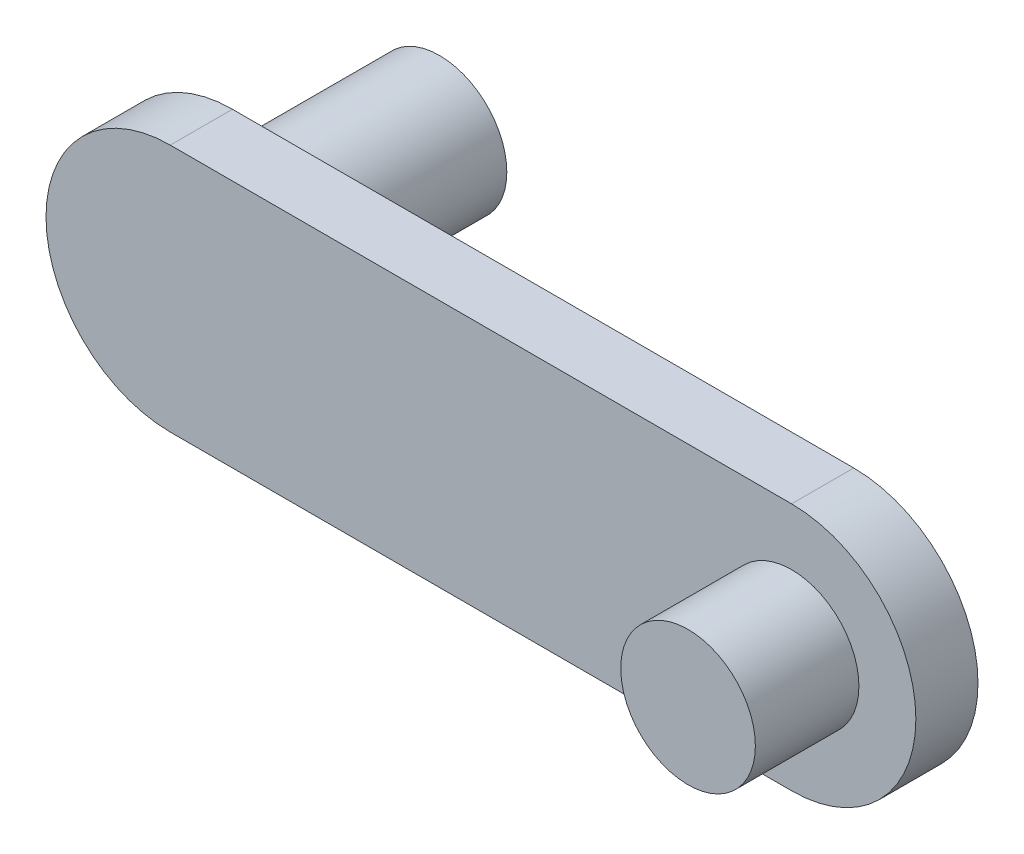
SolidWorks part; units mm, degrees
ref_plane "Ön Düzlem" through (0, 0, 0) normal (0, 0, 1) x (1, 0, 0)
ref_plane "Üst Düzlem" through (0, 0, 0) normal (0, 1, 0) x (1, 0, 0)
ref_plane "Sağ Düzlem" through (0, 0, 0) normal (1, 0, 0) x (0, 0, -1)
sketch "Çizim1" plane through (0, 0, 0) normal (0, 0, 1) x (1, 0, 0)
  line L0 (-15, 0) -> (15, 0) construction
  line L1 (-15, 6) -> (15, 6)
  line L2 (-15, -6) -> (15, -6)
  arc A0 (-15, 6) -> (-15, -6) centre (-15, 0) ccw
  arc A1 (15, -6) -> (15, 6) centre (15, 0) ccw
  point P3 (0, 0)
  dimension "D2" = 6
  dimension "D1" = 30
extrude "Yükseklik-Ekstrüzyon1" add sketch "Çizim1" along normal blind 3
sketch "Çizim2" plane through (0, 0, 3) normal (0, 0, 1) x (1, 0, 0)
  circle A0 centre (15, 0) radius 3.25
  dimension "D1" = 6.5
extrude "Yükseklik-Ekstrüzyon2" add sketch "Çizim2" along normal blind 5
sketch "Çizim3" plane through (0, 0, 0) normal (0, 0, -1) x (-1, 0, 0)
  circle A0 centre (15, 0) radius 3.25
  dimension "D1" = 6.5
extrude "Yükseklik-Ekstrüzyon3" add sketch "Çizim3" along normal blind 10
